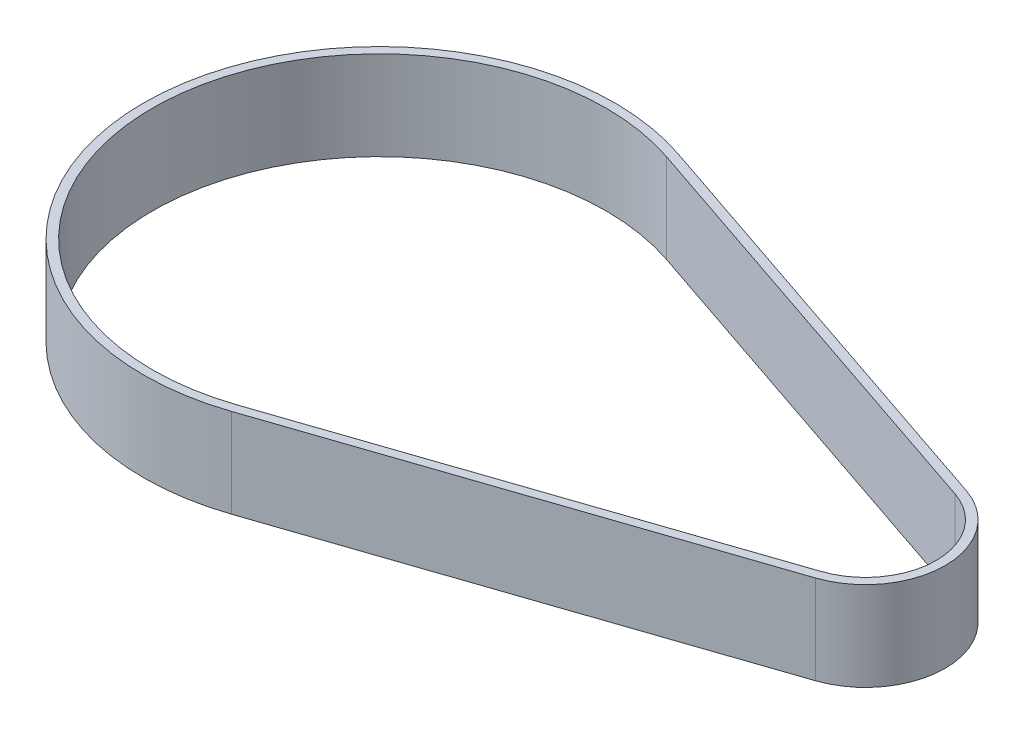
SolidWorks part; units mm, degrees
ref_plane "Alzado" through (0, 0, 0) normal (1, 0, 0) x (0, 1, 0)
ref_plane "Planta" through (0, 0, 0) normal (0, 0, 1) x (0, 1, 0)
ref_plane "Vista lateral" through (0, 0, 0) normal (0, 1, 0) x (-1, 0, 0)
sketch "Croquis1" plane through (0, 0, 0) normal (0, 1, 0) x (-1, 0, 0)
  line L0 (0, 0) -> (54.6, 0) construction
  line L1 (-2.5503, 7.5299) -> (46.4311, 24.1192)
  line L2 (-2.5503, -7.5299) -> (46.4311, -24.1192)
  line L3 (-2.871, 8.477) -> (46.1104, 25.0664)
  line L4 (-2.871, -8.477) -> (46.1104, -25.0664)
  arc A0 (-2.5503, 7.5299) -> (-2.5503, -7.5299) centre (0, 0) ccw
  arc A1 (46.4311, -24.1192) -> (46.4311, 24.1192) centre (54.6, 0) ccw
  arc A2 (46.1104, -25.0664) -> (46.1104, 25.0664) centre (54.6, 0) ccw
  arc A3 (-2.871, 8.477) -> (-2.871, -8.477) centre (0, 0) ccw
  dimension "D1" = 15.9
  dimension "D2" = 50.93
  dimension "D3" = 54.6
  dimension "D4" = 1
extrude "Saliente-Extruir1" add sketch "Croquis1" along normal mid plane 10
equation "\"Dp1\"= 15.9"
equation "\"Dp2\"= 50.93"
equation "\"Lp\"= 220"
equation "\"e\"= 1"
equation "\"D1@Croquis1\"=\"Dp1\""
equation "\"D2@Croquis1\"=\"Dp2\""
equation "\"B\"= 10"
equation "\"D1@Saliente-Extruir1\"=\"B\""
